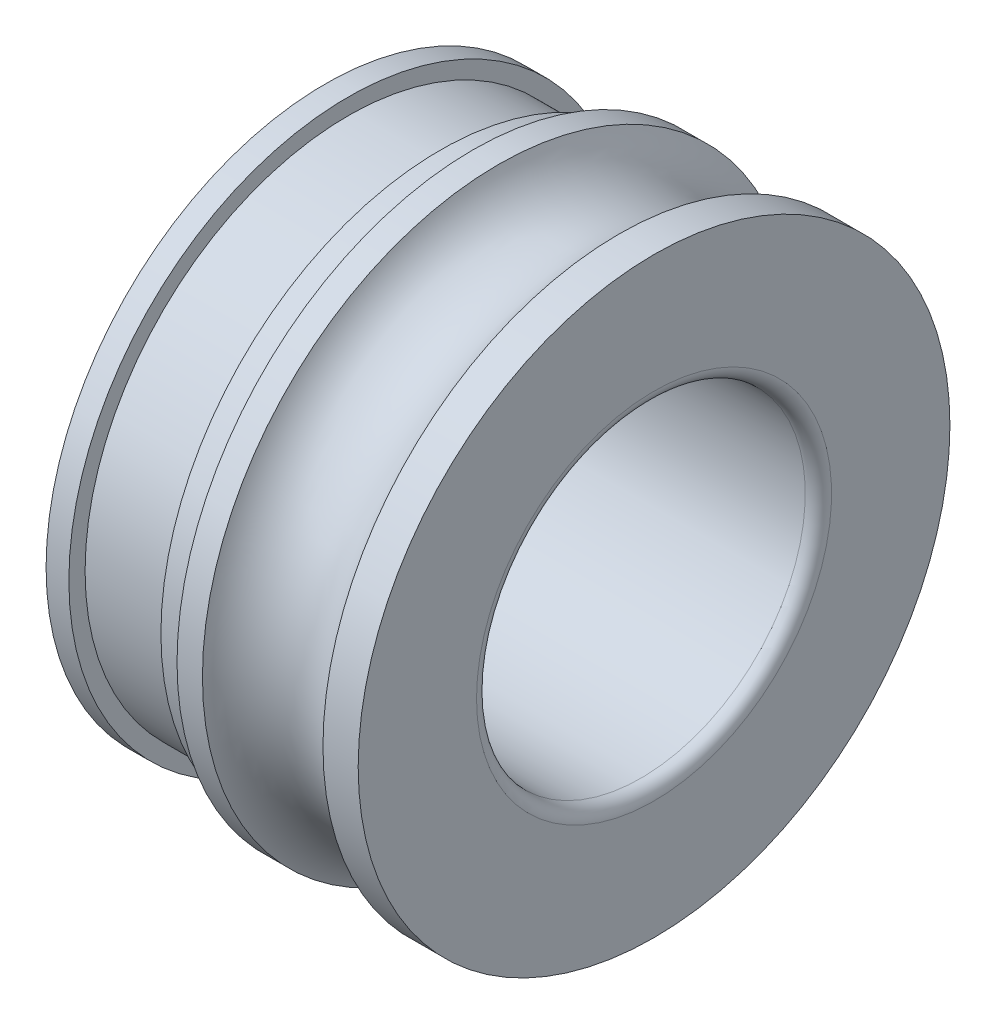
SolidWorks part; units mm, degrees
ref_plane "Plan1" through (0, 0, 0) normal (0, 0, 1) x (1, 0, 0)
ref_plane "Plan2" through (0, 0, 0) normal (0, 1, 0) x (1, 0, 0)
ref_plane "Plan3" through (0, 0, 0) normal (1, 0, 0) x (0, 0, -1)
sketch "Esquisse1" plane through (0, 0, 0) normal (0, 0, 1) x (1, 0, 0)
  line L0 (0, 0) -> (50, 0) construction
  line L1 (1, 12.5) -> (24, 12.5)
  line L2 (11.224, 22.5) -> (13.1562, 22.5)
  line L3 (25, 13.5) -> (25, 22.5)
  line L4 (0, 13.5) -> (0, 20)
  line L5 (11.224, 22.5) -> (11.2322, 21.25)
  line L7 (22.3214, 22.5) -> (25, 22.5)
  line L8 (8.7322, 20) -> (1.7322, 20)
  line L9 (11.2322, 21.25) -> (8.7322, 21.2337)
  line L10 (8.7322, 20) -> (8.7322, 27) construction
  line L11 (8.7322, 21.2337) -> (8.7322, 20)
  line L12 (1.7322, 21.2337) -> (0, 21.2337)
  line L13 (1.7322, 27) -> (1.7322, 20) construction
  line L14 (0, 21.2337) -> (0, 20)
  line L15 (1.7322, 21.2337) -> (1.7322, 20)
  arc A0 (13.1562, 22.5) -> (22.3214, 22.5) centre (17.7388, 24.5) ccw
  arc A1 (25, 13.5) -> (24, 12.5) centre (24, 13.5) cw
  arc A2 (1, 12.5) -> (0, 13.5) centre (1, 13.5) cw
  dimension "D1" = 2.5
revolve "Base-Révolution" add sketch "Esquisse1" angle 360 about L0
